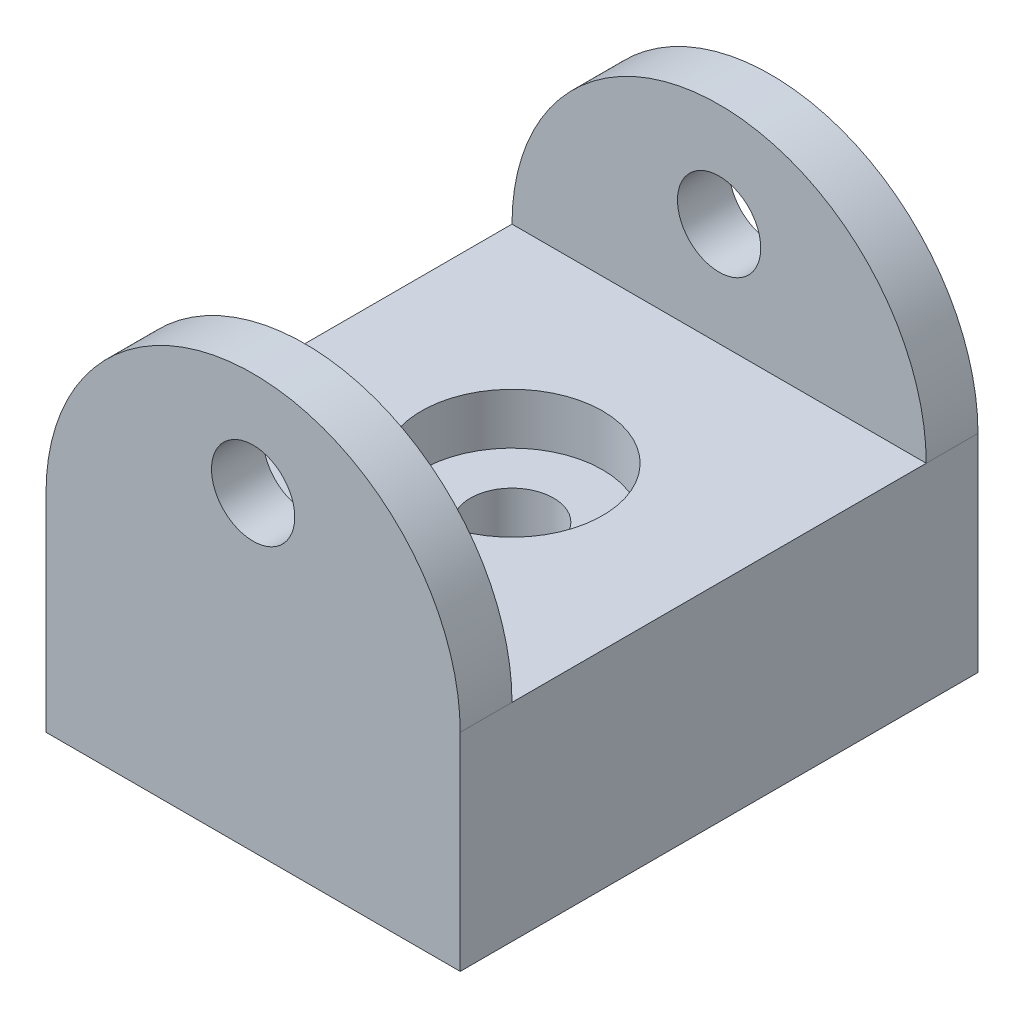
SolidWorks part; units mm, degrees
ref_plane "Front Plane" through (0, 0, 0) normal (0, 0, 1) x (1, 0, 0)
ref_plane "Top Plane" through (0, 0, 0) normal (0, 1, 0) x (1, 0, 0)
ref_plane "Right Plane" through (0, 0, 0) normal (1, 0, 0) x (0, 0, -1)
sketch "Sketch1" plane through (0, 0, 0) normal (0, 0, 1) x (1, 0, 0)
  line L0 (-12.7, 0) -> (-12.7, -12.7)
  line L1 (-12.7, -12.7) -> (12.7, -12.7)
  line L2 (12.7, -12.7) -> (12.7, 0)
  arc A0 (-12.7, 0) -> (12.7, 0) centre (0, 0) cw
  point P6 (0, 12.7)
  point P7 (0, -12.7)
  dimension "D1" = 25.4
  dimension "D2" = 25.4
extrude "Boss-Extrude1" add sketch "Sketch1" along normal mid plane 31.75
sketch "Sketch3" plane through (12.7, 0, 0) normal (1, 0, 0) x (0, 0, -1)
  line L0 (12.7, 0) -> (-12.7, 0)
  line L1 (-15.875, 0) -> (15.875, 0) construction
  line L2 (-12.7, 0) -> (-12.7, 12.7)
  line L3 (15.875, 12.7) -> (-15.875, 12.7) construction
  line L4 (-12.7, 12.7) -> (12.7, 12.7)
  line L5 (12.7, 12.7) -> (12.7, 0)
  point P6 (0, 0)
  dimension "D1" = 25.4
extrude "Cut-Extrude1" cut sketch "Sketch3" against normal through all
hole_wizard "#10 Clearance Hole1" positions "Sketch4" profile "Sketch5" hole size "#10" standard "ANSI Inch" end condition through all
sketch "Sketch4" plane through (0, 0, 15.875) normal (0, 0, 1) x (1, 0, 0)
  line L0 (0, 0) -> (0, 12.7) construction
  arc A0 (12.7, 0) -> (-12.7, 0) centre (0, 0) ccw construction
  point P8 (0, 6.35)
sketch "Sketch5" plane through (0, 6.35, 15.875) normal (1, 0, 0) x (0, -1, 0)
  line L0 (0, 0) -> (0, 31.75)
  line L1 (0, 31.75) -> (2.5527, 31.75)
  line L2 (2.5527, 31.75) -> (2.5527, 0)
  line L5 (2.5527, 0) -> (0, 0)
  line L11 (0, -6.35) -> (0, 107.95) construction
  dimension "Thru Hole Dia." = 5.1054
  dimension "Thru Hole Depth" = 31.75
hole_wizard "CBORE for #10 Binding Head Machine Screw1" positions "Sketch6" profile "Sketch7" counterbore size "#10" standard "ANSI Inch" end condition through all
sketch "Sketch6" plane through (0, 0, 0) normal (0, 1, 0) x (1, 0, 0)
  point P0 (0, 0)
sketch "Sketch7" plane through (0, 0, 0) normal (1, 0, 0) x (0, 0, 1)
  line L0 (0, 0) -> (0, 12.7)
  line L1 (0, 12.7) -> (2.5527, 12.7)
  line L3 (2.5527, 12.7) -> (2.5527, 3.1242)
  line L4 (2.5527, 3.1242) -> (5.5562, 3.1242)
  line L5 (5.5562, 3.1242) -> (5.5562, 0)
  line L7 (5.5562, 0) -> (0, 0)
  line L11 (0, -6.35) -> (0, 107.95) construction
  dimension "Thru Hole Dia." = 5.1054
  dimension "Thru Hole Depth" = 12.7
  dimension "C'Bore Dia." = 11.1125
  dimension "C'Bore Depth" = 3.1242
